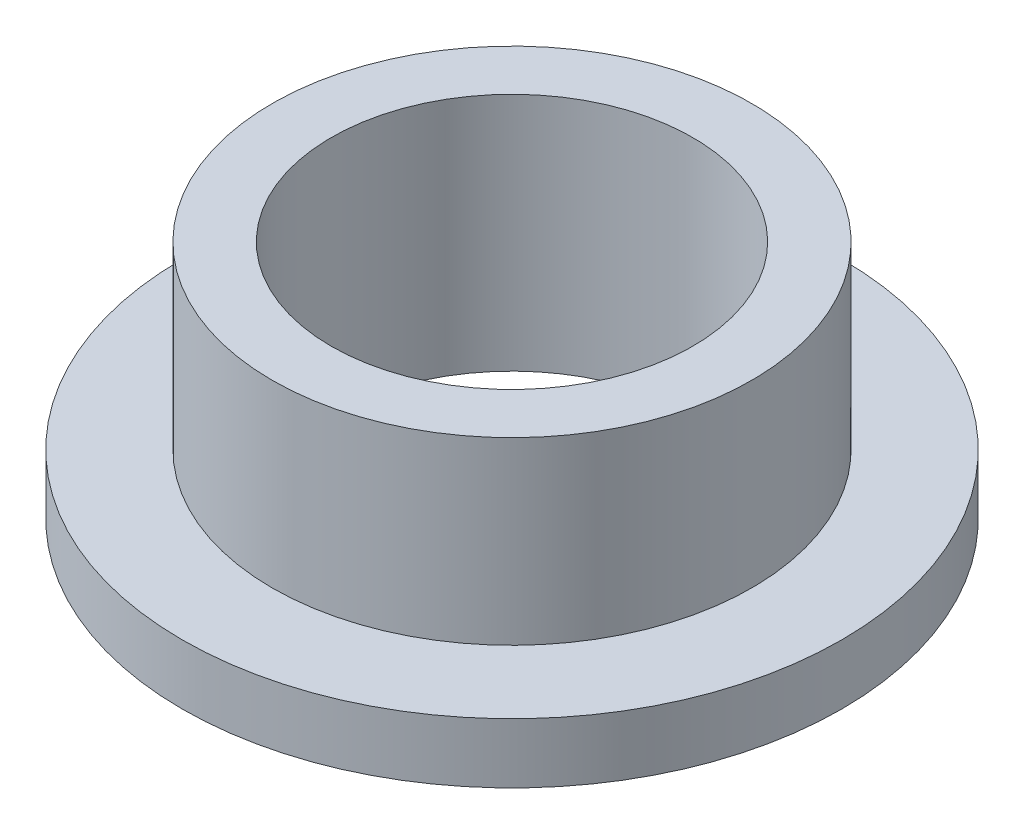
SolidWorks part; units mm, degrees
material "Leaded Commercial Bronze"
ref_plane "Front" through (0, 0, 0) normal (0, 0, 1) x (1, 0, 0)
ref_plane "Top" through (0, 0, 0) normal (0, 1, 0) x (1, 0, 0)
ref_plane "Right" through (0, 0, 0) normal (1, 0, 0) x (0, 0, -1)
sketch "Sketch1" plane through (0, 0, 0) normal (0, 1, 0) x (1, 0, 0)
  circle A0 centre (0, 0) radius 4.7879
  circle A1 centre (0, 0) radius 6.35
  circle A2 centre (0, 0) radius 8.7312
  dimension "ID" = 9.5758
  dimension "OD" = 12.7
  dimension "FlangeOD" = 17.4625
sketch "Sketch2" plane through (0, 0, 0) normal (0, 1, 0) x (1, 0, 0)
  circle A0 centre (0, 0) radius 4.7879 construction
  circle A1 centre (0, 0) radius 6.35 construction
  circle A2 centre (0, 0) radius 4.7879
  circle A3 centre (0, 0) radius 6.35
extrude "Boss-Extrude1" add sketch "Sketch2" along normal blind 6.35
sketch "Sketch3" plane through (0, 0, 0) normal (0, 1, 0) x (1, 0, 0)
  circle A0 centre (0, 0) radius 8.7312 construction
  circle A1 centre (0, 0) radius 6.35 construction
  circle A2 centre (0, 0) radius 8.7312
  circle A3 centre (0, 0) radius 6.35
extrude "Boss-Extrude2" add sketch "Sketch3" along normal blind 1.5875
